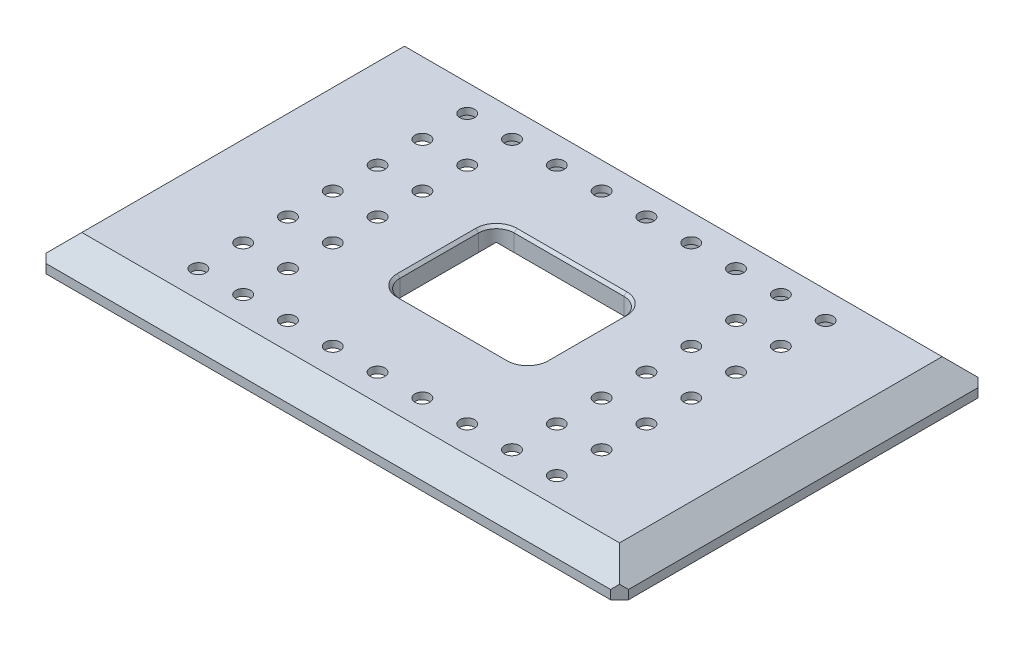
SolidWorks part; units mm, degrees
ref_plane "Front Plane" through (0, 0, 0) normal (0, 0, 1) x (1, 0, 0)
ref_plane "Top Plane" through (0, 0, 0) normal (0, 1, 0) x (1, 0, 0)
ref_plane "Right Plane" through (0, 0, 0) normal (1, 0, 0) x (0, 0, -1)
sketch "Sketch1" plane through (0, 0, 0) normal (0, 1, 0) x (1, 0, 0)
  line L1 (-65, -41) -> (65, -41)
  line L2 (-65, -41) -> (-65, 41)
  line L3 (-65, 41) -> (65, 41)
  line L4 (65, -41) -> (65, 41)
  line L5 (-65, -41) -> (65, 41) construction
  line L6 (-65, 41) -> (65, -41) construction
  point P0 (0, 0)
  dimension "D1" = 130
  dimension "D2" = 82
extrude "Boss-Extrude1" add sketch "Sketch1" along normal blind 2
sketch "Sketch2" plane through (0, 2, 0) normal (0, 1, 0) x (1, 0, 0)
  line L4 (65, -41) -> (65, 41)
  line L5 (65, 41) -> (-65, 41)
  line L6 (-65, 41) -> (-65, -41)
  line L7 (-65, -41) -> (65, -41)
  line L8 (65, -41) -> (65, 41)
  line L9 (65, 41) -> (-65, 41)
  line L10 (-65, 41) -> (-65, -41)
  line L11 (-65, -41) -> (65, -41)
  dimension "D1" = 0
ref_plane "Plane1" through (0, 7, 0) normal (0, 1, 0) x (1, 0, 0)
sketch "Sketch3" plane through (0, 7, 0) normal (0, 1, 0) x (1, 0, 0)
  line L0 (-65, 41) -> (-65, -41) construction
  line L1 (-60, -36) -> (60, -36)
  line L2 (-60, -36) -> (-60, 36)
  line L3 (-60, 36) -> (60, 36)
  line L4 (60, -36) -> (60, 36)
  line L5 (-60, -36) -> (60, 36) construction
  line L6 (-60, 36) -> (60, -36) construction
  line L7 (65, 41) -> (-65, 41) construction
  point P0 (0, 0)
  dimension "D1" = 5
  dimension "D2" = 5
loft "Loft1" add profiles "Sketch3", "Sketch2"
chamfer "Chamfer2" distance 2 angle 45 4 edges at (65, 1, 41) (65, 1, -41) (-65, 1, -41) (-65, 1, 41)
sketch "Sketch4" plane through (0, 0, 0) normal (0, -1, 0) x (1, 0, 0)
  line L0 (-65, -39) -> (-65, 39) construction
  line L1 (-57.9, 15) -> (-49.9, 15)
  line L2 (-57.9, 15) -> (-57.9, 25)
  line L3 (-57.9, 25) -> (-49.9, 25)
  line L4 (-49.9, 15) -> (-49.9, 25)
  line L5 (-57.9, 15) -> (-49.9, 25) construction
  line L6 (-57.9, 25) -> (-49.9, 15) construction
  line L7 (-65, 0) -> (65, 0) construction
  line L8 (65, 39) -> (65, -39) construction
  line L9 (0, 41) -> (0, -41) construction
  line L10 (-63, 41) -> (63, 41) construction
  line L11 (63, -41) -> (-63, -41) construction
  line L12 (-57.9, -25) -> (-49.9, -15) construction
  line L13 (-57.9, -15) -> (-49.9, -25) construction
  line L14 (-49.9, -15) -> (-49.9, -25)
  line L15 (-57.9, -25) -> (-49.9, -25)
  line L16 (-57.9, -15) -> (-57.9, -25)
  line L17 (-57.9, -15) -> (-49.9, -15)
  line L18 (57.9, -15) -> (49.9, -25) construction
  line L19 (57.9, -25) -> (49.9, -15) construction
  line L20 (57.9, 25) -> (49.9, 15) construction
  line L21 (57.9, 15) -> (49.9, 25) construction
  line L22 (57.9, -15) -> (49.9, -15)
  line L23 (57.9, -15) -> (57.9, -25)
  line L24 (57.9, -25) -> (49.9, -25)
  line L25 (49.9, -15) -> (49.9, -25)
  line L26 (49.9, 15) -> (49.9, 25)
  line L27 (57.9, 25) -> (49.9, 25)
  line L28 (57.9, 15) -> (57.9, 25)
  line L29 (57.9, 15) -> (49.9, 15)
  point P0 (-53.9, 20)
  point P21 (-53.9, -20)
  point P30 (53.9, -20)
  point P31 (53.9, 20)
  dimension "D1" = 10
  dimension "D2" = 7.1
  dimension "D3" = 8
  dimension "D4" = 40
extrude "Boss-Extrude2" add sketch "Sketch4" along normal blind 7
sketch "Sketch5" plane through (-57.9, 0, 0) normal (-1, 0, 0) x (0, 0, 1)
  line L0 (-15, 0) -> (-25, -7) construction
  line L1 (0, 0) -> (0, 50000) construction
  circle A0 centre (-20, -3.5) radius 2.05
  circle A1 centre (20, -3.5) radius 2.05
  dimension "D1" = 4.1
extrude "Cut-Extrude1" cut sketch "Sketch5" against normal through all
sketch "Sketch6" plane through (0, 0, 0) normal (0, -1, 0) x (1, 0, 0)
  line L0 (49.9, 25) -> (49.9, 15) construction
  line L1 (-48.9, -35) -> (48.9, -35)
  line L2 (-48.9, -35) -> (-48.9, 35)
  line L3 (-48.9, 35) -> (48.9, 35)
  line L4 (48.9, -35) -> (48.9, 35)
  line L5 (-48.9, -35) -> (48.9, 35) construction
  line L6 (-48.9, 35) -> (48.9, -35) construction
  line L8 (-60, 36) -> (60, 36) construction
  point P0 (0, 0)
  dimension "D1" = 1
  dimension "D2" = 1
extrude "Cut-Extrude2" cut sketch "Sketch6" against normal offset from surface (5.5 mm away) 1.5 up to face at (0, 7, 0)
sketch "Sketch7" plane through (0, 5.5, 0) normal (0, -1, 0) x (1, 0, 0)
  line L0 (0, 35) -> (0, -35) construction
  line L1 (-48.9, 35) -> (48.9, 35) construction
  line L2 (-48.9, -35) -> (48.9, -35) construction
  line L3 (-48.9, 0) -> (48.9, 0) construction
  line L4 (-48.9, -35) -> (-48.9, 35) construction
  line L5 (48.9, 35) -> (48.9, -35) construction
  circle A0 centre (0, 0) radius 1.65
  circle A1 centre (10, 0) radius 1.65
  circle A2 centre (20, 0) radius 1.65
  circle A3 centre (30, 0) radius 1.65
  circle A4 centre (40, 0) radius 1.65
  circle A7 centre (10, 10) radius 1.65
  circle A8 centre (20, 10) radius 1.65
  circle A9 centre (30, 10) radius 1.65
  circle A10 centre (40, 10) radius 1.65
  circle A13 centre (10, 20) radius 1.65
  circle A14 centre (20, 20) radius 1.65
  circle A15 centre (30, 20) radius 1.65
  circle A16 centre (40, 20) radius 1.65
  circle A19 centre (10, 30) radius 1.65
  circle A20 centre (20, 30) radius 1.65
  circle A21 centre (30, 30) radius 1.65
  circle A22 centre (40, 30) radius 1.65
  circle A25 centre (0, 10) radius 1.65
  circle A26 centre (0, 20) radius 1.65
  circle A27 centre (0, 30) radius 1.65
  circle A36 centre (-40, 30) radius 1.65
  circle A37 centre (-30, 30) radius 1.65
  circle A38 centre (-20, 30) radius 1.65
  circle A39 centre (-10, 30) radius 1.65
  circle A41 centre (-40, 20) radius 1.65
  circle A42 centre (-30, 20) radius 1.65
  circle A43 centre (-20, 20) radius 1.65
  circle A44 centre (-10, 20) radius 1.65
  circle A46 centre (-40, 10) radius 1.65
  circle A47 centre (-30, 10) radius 1.65
  circle A48 centre (-20, 10) radius 1.65
  circle A49 centre (-10, 10) radius 1.65
  circle A51 centre (-40, 0) radius 1.65
  circle A52 centre (-30, 0) radius 1.65
  circle A53 centre (-20, 0) radius 1.65
  circle A54 centre (-10, 0) radius 1.65
  circle A55 centre (-10, -10) radius 1.65
  circle A56 centre (-20, -10) radius 1.65
  circle A57 centre (-30, -10) radius 1.65
  circle A58 centre (-40, -10) radius 1.65
  circle A60 centre (-10, -20) radius 1.65
  circle A61 centre (-20, -20) radius 1.65
  circle A62 centre (-30, -20) radius 1.65
  circle A63 centre (-40, -20) radius 1.65
  circle A65 centre (-10, -30) radius 1.65
  circle A66 centre (-20, -30) radius 1.65
  circle A67 centre (-30, -30) radius 1.65
  circle A68 centre (-40, -30) radius 1.65
  circle A70 centre (0, -30) radius 1.65
  circle A71 centre (0, -20) radius 1.65
  circle A72 centre (0, -10) radius 1.65
  circle A74 centre (40, -30) radius 1.65
  circle A75 centre (30, -30) radius 1.65
  circle A76 centre (20, -30) radius 1.65
  circle A77 centre (10, -30) radius 1.65
  circle A79 centre (40, -20) radius 1.65
  circle A80 centre (30, -20) radius 1.65
  circle A81 centre (20, -20) radius 1.65
  circle A82 centre (10, -20) radius 1.65
  circle A84 centre (40, -10) radius 1.65
  circle A85 centre (30, -10) radius 1.65
  circle A86 centre (20, -10) radius 1.65
  circle A87 centre (10, -10) radius 1.65
  dimension "D1" = 3.3
  dimension "D2" = 5
  dimension "D3" = 4
extrude "Cut-Extrude3" cut sketch "Sketch7" against normal through all
sketch "Sketch9" plane through (0, 7, 0) normal (0, 1, 0) x (1, 0, 0)
  circle A0 centre (-30, 20) radius 1.65 construction
  circle A1 centre (-40, 20) radius 1.65 construction
  circle A2 centre (-40, 30) radius 1.65 construction
  circle A3 centre (-30, 30) radius 1.65 construction
  circle A4 centre (-30, 20) radius 1.65
  circle A5 centre (-40, 20) radius 1.65
  circle A6 centre (-40, 30) radius 1.65
  circle A7 centre (-30, 30) radius 1.65
sketch "Sketch10" plane through (0, 7, 0) normal (0, 1, 0) x (1, 0, 0)
  line L1 (-25, -25) -> (25, -25)
  line L2 (-25, -25) -> (-25, 25)
  line L3 (-25, 25) -> (25, 25)
  line L4 (25, -25) -> (25, 25)
  line L5 (-25, -25) -> (25, 25) construction
  line L6 (-25, 25) -> (25, -25) construction
  point P0 (0, 0)
  dimension "D1" = 50
extrude "Boss-Extrude3" add sketch "Sketch10" against normal up to surface (1.5 mm away) up to face at (10, 5.5, -1.65)
sketch "Sketch11" plane through (0, 5.5, 0) normal (0, -1, 0) x (1, 0, 0)
  line L1 (-22.5, -20) -> (22.5, -20)
  line L2 (-22.5, -20) -> (-22.5, 20)
  line L3 (-22.5, 20) -> (22.5, 20)
  line L4 (22.5, -20) -> (22.5, 20)
  line L5 (-22.5, -20) -> (22.5, 20) construction
  line L6 (-22.5, 20) -> (22.5, -20) construction
  point P0 (0, 0)
  dimension "D1" = 45
  dimension "D2" = 40
extrude "Boss-Extrude4" add sketch "Sketch11" along normal blind 3.5
sketch "Sketch12" plane through (0, 7, 0) normal (0, 1, 0) x (1, 0, 0)
  line L1 (-16.25, -12.75) -> (16.25, -12.75)
  line L2 (-16.25, -12.75) -> (-16.25, 12.75)
  line L3 (-16.25, 12.75) -> (16.25, 12.75)
  line L4 (16.25, -12.75) -> (16.25, 12.75)
  line L5 (-16.25, -12.75) -> (16.25, 12.75) construction
  line L6 (-16.25, 12.75) -> (16.25, -12.75) construction
  line L7 (-18.21, -14.785) -> (18.21, -14.785) construction
  line L8 (-18.21, -14.785) -> (-18.21, 14.785) construction
  line L9 (-18.21, 14.785) -> (18.21, 14.785) construction
  line L10 (18.21, -14.785) -> (18.21, 14.785) construction
  line L11 (-18.21, -14.785) -> (18.21, 14.785) construction
  line L12 (-18.21, 14.785) -> (18.21, -14.785) construction
  circle A0 centre (-18.21, 14.785) radius 1.35
  circle A1 centre (18.21, 14.785) radius 1.35
  circle A2 centre (18.21, -14.785) radius 1.35
  circle A3 centre (-18.21, -14.785) radius 1.35
  point P0 (0, 0)
  point P6 (0, 0)
  dimension "D3" = 2.7
  dimension "D1" = 32.5
  dimension "D2" = 25.5
  dimension "D4" = 36.42
  dimension "D5" = 29.57
extrude "Cut-Extrude4" cut sketch "Sketch12" against normal through all
chamfer "Chamfer3" distance 0.6 angle 45 4 edges at (0, 2, 12.75) (16.25, 2, 0) (-16.25, 2, 0) (0, 2, -12.75)
fillet "Fillet1" radius 4 4 edges at (16.25, 4.8, 12.75) (-16.25, 4.8, 12.75) (16.25, 4.8, -12.75) (-16.25, 4.8, -12.75)
chamfer "Chamfer4" distance 0.6 angle 45 8 edges at (0, 7, -12.75) (-15.0784, 7, -11.5784) (15.0784, 7, -11.5784) (-16.25, 7, 0) (16.25, 7, 0) (-15.0784, 7, 11.5784) (15.0784, 7, 11.5784) (0, 7, 12.75)
sketch "Sketch13" plane through (0, 7, 0) normal (0, 1, 0) x (1, 0, 0)
  circle A0 centre (-18.21, -14.785) radius 1.35 construction
  circle A1 centre (18.21, -14.785) radius 1.35 construction
  circle A2 centre (18.21, 14.785) radius 1.35 construction
  circle A3 centre (-18.21, 14.785) radius 1.35 construction
  circle A4 centre (-18.21, -14.785) radius 1.35
  circle A5 centre (18.21, -14.785) radius 1.35
  circle A6 centre (18.21, 14.785) radius 1.35
  circle A7 centre (-18.21, 14.785) radius 1.35
extrude "Boss-Extrude5" add sketch "Sketch13" against normal blind 1
sketch "Sketch14" plane through (0, 2, 0) normal (0, -1, 0) x (1, 0, 0)
  circle A0 centre (-18.21, 14.785) radius 1.8
  circle A1 centre (18.21, 14.785) radius 1.8
  circle A2 centre (18.21, -14.785) radius 1.8
  circle A3 centre (-18.21, -14.785) radius 1.8
  dimension "D1" = 3.6
extrude "Cut-Extrude5" cut sketch "Sketch14" against normal up to surface (4 mm away) up to face at (-18.21, 6, 16.135)
chamfer "Chamfer5" distance 2 angle 45 4 edges at (0, 2, -20) (-22.5, 2, 0) (0, 2, 20) (22.5, 2, 0)
